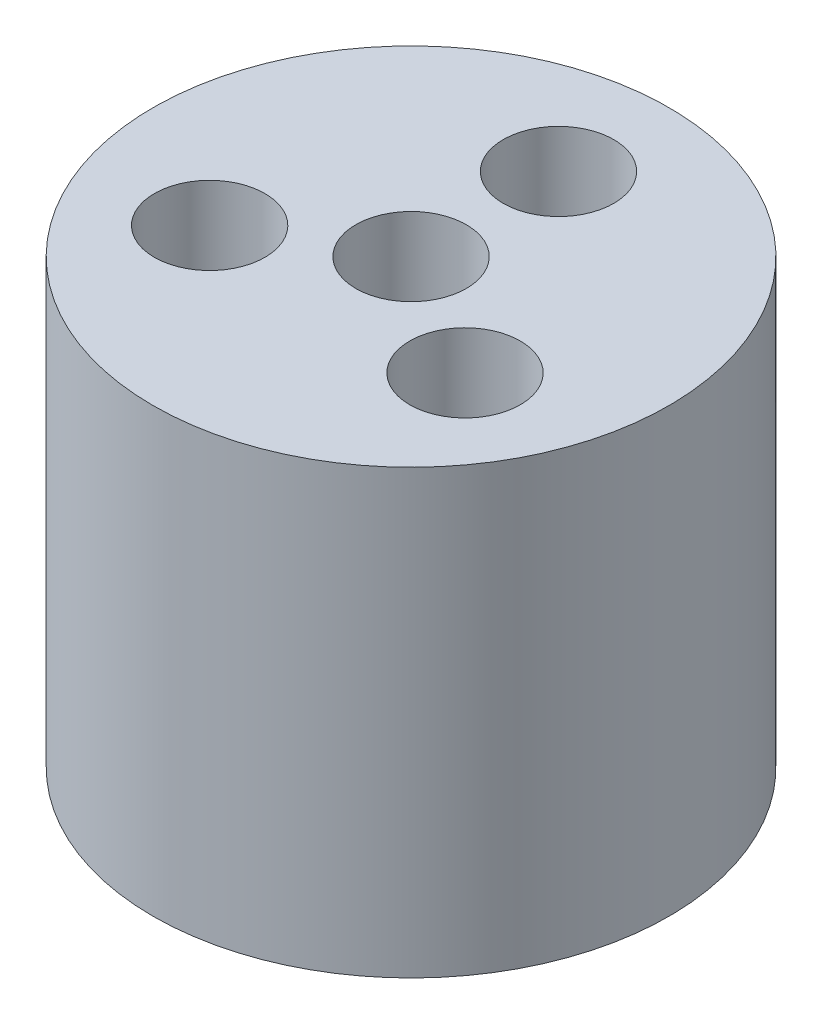
SolidWorks part; units mm, degrees
ref_plane "정면" through (0, 0, 0) normal (0, 0, 1) x (1, 0, 0)
ref_plane "윗면" through (0, 0, 0) normal (0, 1, 0) x (1, 0, 0)
ref_plane "우측면" through (0, 0, 0) normal (1, 0, 0) x (0, 0, -1)
sketch "스케치1" plane through (0, 0, 0) normal (0, 1, 0) x (1, 0, 0)
  circle A0 centre (0, 0) radius 14
  dimension "D1" = 28
extrude "보스-돌출1" add sketch "스케치1" along normal mid plane 24
hole_wizard "Ø6.0 (6) 지름 구멍1" positions "스케치2" profile "스케치3" hole size "Ø6.0" standard "KS" end condition through all
sketch "스케치2" plane through (0, 12, 0) normal (0, 1, 0) x (1, 0, 0)
  point P0 (0, 0)
sketch "스케치3" plane through (0, 12, 0) normal (1, 0, 0) x (0, 0, 1)
  line L0 (0, 0) -> (0, 24)
  line L1 (0, 24) -> (3, 24)
  line L2 (3, 24) -> (3, 0)
  line L5 (3, 0) -> (0, 0)
  line L11 (0, -6.35) -> (0, 107.95) construction
  dimension "관통 구멍 지름" = 6
  dimension "관통 구멍 깊이" = 24
hole_wizard "Ø6.0 (6) 지름 구멍2" positions "스케치4" profile "스케치5" hole size "Ø6.0" standard "KS" end condition through all
sketch "스케치4" plane through (0, 12, 0) normal (0, 1, 0) x (1, 0, 0)
  point P0 (0, 8)
  dimension "D1" = 8
sketch "스케치5" plane through (0, 12, -8) normal (1, 0, 0) x (0, 0, 1)
  line L0 (0, 0) -> (0, 24)
  line L1 (0, 24) -> (3, 24)
  line L2 (3, 24) -> (3, 0)
  line L5 (3, 0) -> (0, 0)
  line L11 (0, -6.35) -> (0, 107.95) construction
  dimension "관통 구멍 지름" = 6
  dimension "관통 구멍 깊이" = 24
pattern_circular "원형 패턴1" count 3 over 360 about axis through (0, 0, 0) along (0, 1, 0) of "Ø6.0 (6) 지름 구멍2"
